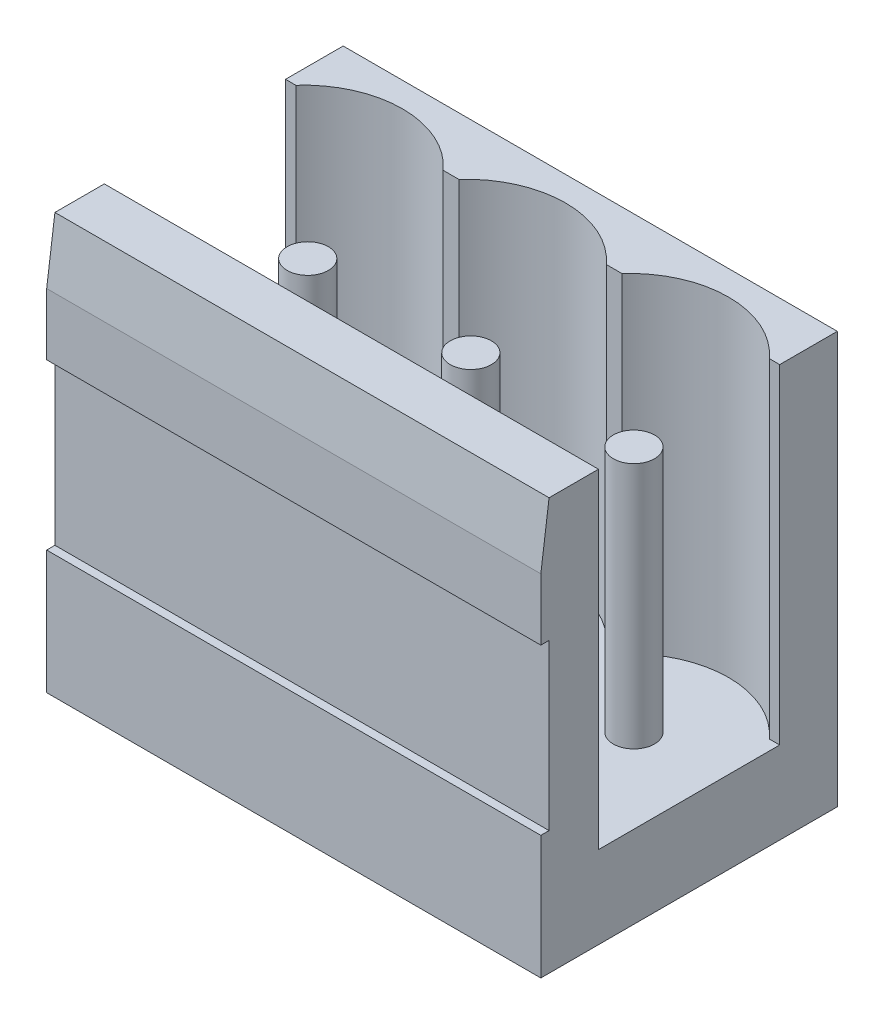
SolidWorks part; units mm, degrees
ref_plane "前视基准面" through (0, 0, 0) normal (0, 0, 1) x (1, 0, 0)
ref_plane "上视基准面" through (0, 0, 0) normal (0, 1, 0) x (1, 0, 0)
ref_plane "右视基准面" through (0, 0, 0) normal (1, 0, 0) x (0, 0, -1)
sketch "草图1" plane through (0, 0, 0) normal (0, 0, 1) x (1, 0, 0)
  line L0 (0, 0) -> (12, 0)
  line L1 (12, 0) -> (12, 10)
  line L2 (12, 10) -> (0, 10)
  line L3 (0, 10) -> (0, 0)
  dimension "D1" = 12
  dimension "D2" = 10
extrude "凸台-拉伸1" add sketch "草图1" along normal blind 7.2
sketch "草图2" plane through (12, 0, 0) normal (1, 0, 0) x (0, 0, -1)
  line L0 (-8.1771, 3) -> (-7, 3)
  line L1 (-7, 3) -> (-7, 7)
  line L2 (-7, 7) -> (-8.1771, 7)
  line L3 (-7.2, 0) -> (0, 0) construction
  line L4 (-7.2, 10) -> (0, 10) construction
  line L5 (-7.2, 0) -> (-7.2, 10) construction
  line L6 (-8.1771, 7) -> (-8.1771, 3)
  point P2 (-3.6, 0)
  dimension "D1" = 3
  dimension "D2" = 3
  dimension "D3" = 0.2
extrude "切除-拉伸1" cut sketch "草图2" against normal through all
sketch "草图3" plane through (12, 0, 0) normal (1, 0, 0) x (0, 0, -1)
  line L1 (-7.2, 10) -> (0, 10) construction
  line L2 (-7, 10) -> (-7.2, 8.5)
  line L3 (-7.2, 7) -> (-7.2, 10) construction
  line L4 (-7.2, 8.5) -> (-7.2, 10)
  line L5 (-7.2, 10) -> (-7, 10)
extrude "切除-拉伸2" cut sketch "草图3" against normal through all
sketch "草图4" plane through (0, 0, 0) normal (0, -1, 0) x (1, 0, 0)
  line L0 (5.5, 4.2) -> (6.5, 4.2)
  line L3 (0, 7.2) -> (12, 7.2) construction
  line L4 (6, 4.2) -> (6, 0) construction
  line L5 (0, 0) -> (12, 0) construction
  line L6 (6.5, 4.2) -> (6.5, 0)
  line L7 (5.5, 4.2) -> (5.5, 0)
  line L8 (5.5, 0) -> (6.5, 0)
  dimension "D1" = 3
  dimension "D2" = 1
extrude "切除-拉伸3" cut sketch "草图4" against normal blind 1
pattern_linear "阵列(线性)1" count 2 spacing 3.96 along (1, 0, 0) of "切除-拉伸3"
pattern_linear "阵列(线性)2" count 2 spacing 3.96 along (-1, 0, 0) of "切除-拉伸3"
sketch "草图5" plane through (0, 0, 4.2) normal (0, 0, -1) x (-1, 0, 0)
  line L0 (-1.54, 0) -> (-2.54, 1) construction
  line L1 (-2.54, 0) -> (-1.54, 1) construction
  circle A0 centre (-2.04, 0.5) radius 0.4
  dimension "D1" = 0.8
extrude "凸台-拉伸3" add sketch "草图5" along normal blind 5.8
pattern_linear "阵列(线性)3" count 3 spacing 3.96 along (1, 0, 0) of "凸台-拉伸3"
sketch "草图6" plane through (0, 10, 0) normal (0, 1, 0) x (1, 0, 0)
  line L0 (0, -5.8) -> (12, -5.8)
  line L1 (0, -7) -> (0, 0) construction
  line L2 (12, -7) -> (12, 0) construction
  line L3 (0, -7.2) -> (12, -7.2) construction
  line L4 (12, -0.6) -> (0, -0.6) construction
  line L5 (12, 0) -> (0, 0) construction
  line L6 (6, -0.6) -> (6, -5.8) construction
  line L7 (12, -3) -> (0, -3) construction
  line L8 (12, -1.4) -> (11.7489, -1.4)
  line L9 (12, -4.2643) -> (12, -5.8)
  line L10 (0, -5.8) -> (0, -1.4)
  line L11 (8.1711, -1.4) -> (7.7889, -1.4)
  line L12 (12, -4.2643) -> (12, -1.4)
  line L13 (4.2111, -1.4) -> (3.8289, -1.4)
  line L14 (0.2511, -1.4) -> (0, -1.4)
  arc A0 (7.7889, -1.4) -> (4.2111, -1.4) centre (6, -3) ccw
  arc A1 (11.7489, -1.4) -> (8.1711, -1.4) centre (9.96, -3) ccw
  arc A2 (3.8289, -1.4) -> (0.2511, -1.4) centre (2.04, -3) ccw
  line M1 (0, 0) -> (0, -7)
  line M3 (12, -7) -> (12, 0)
  dimension "D1" = 1.4
  dimension "D2" = 0.6
  dimension "D3" = 3
  dimension "D6" = 1.4
  dimension "D4" = 2
  dimension "D5" = 2
extrude "切除-拉伸4" cut sketch "草图6" against normal blind 8 contours L8 A1 L11 L0 M1 M3
sketch "草图7" plane through (0, 2, 0) normal (0, 1, 0) x (-1, 0, 0)
  line L0 (-6, 5.8) -> (-6, 0) construction
  line L1 (0, 5.8) -> (-12, 5.8) construction
  line L2 (-12, 0) -> (0, 0) construction
  line L3 (-12, 3) -> (0, 3) construction
  line L4 (-12, 5.8) -> (-12, 1.4) construction
  line L5 (0, 1.4) -> (0, 5.8) construction
  circle A0 centre (-6, 2.9) radius 0.5
  circle A1 centre (-9.96, 2.9) radius 0.5
  circle A2 centre (-2.04, 2.9) radius 0.5
  dimension "D2" = 1
  dimension "D1" = 3
  dimension "D3" = 2
  dimension "D4" = 2
extrude "凸台-拉伸4" add sketch "草图7" along normal blind 6
